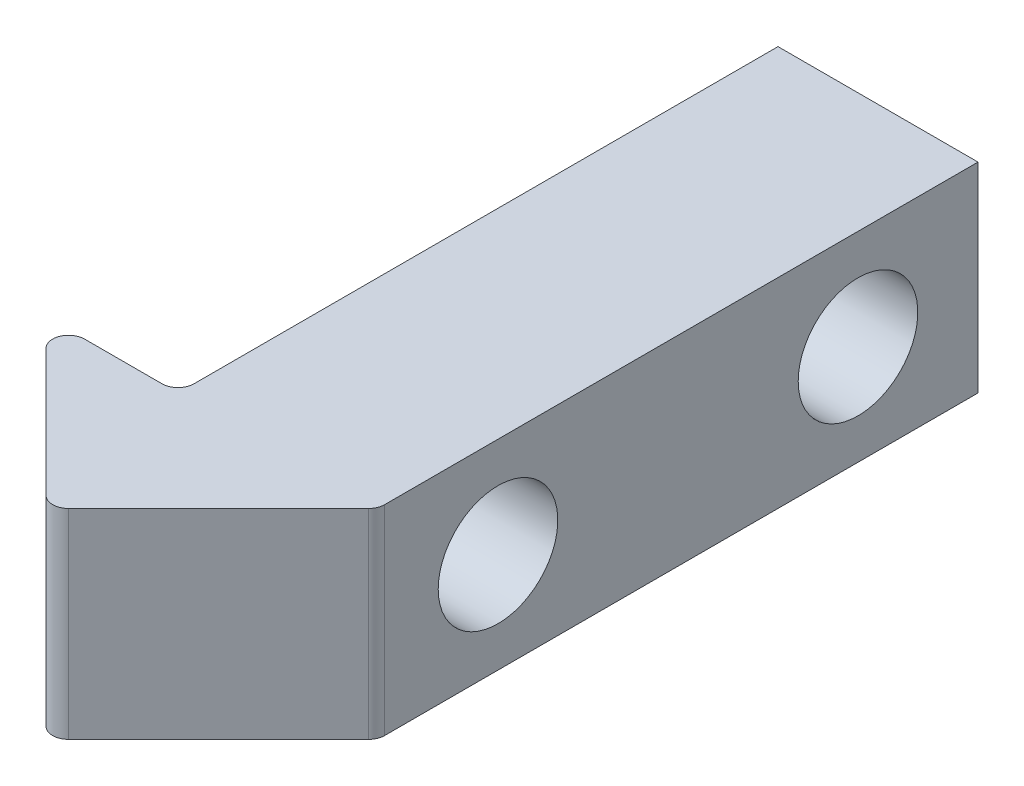
SolidWorks part; units mm, degrees
ref_plane "Front Plane" through (0, 0, 0) normal (0, 0, 1) x (1, 0, 0)
ref_plane "Top Plane" through (0, 0, 0) normal (0, 1, 0) x (1, 0, 0)
ref_plane "Right Plane" through (0, 0, 0) normal (1, 0, 0) x (0, 0, -1)
sketch "Sketch1" plane through (0, 0, 0) normal (0, 1, 0) x (1, 0, 0)
  line L0 (16.8387, -6.35) -> (11.5678, -11.6208)
  line L1 (-16.8387, -12.7) -> (16.8387, -12.7)
  line L2 (-16.8387, -12.7) -> (-16.8387, 12.7)
  line L3 (-16.8387, 12.7) -> (16.8387, 12.7)
  line L4 (16.8387, -12.7) -> (16.8387, 12.7)
  line L5 (-16.8387, -12.7) -> (16.8387, 12.7) construction
  line L6 (-16.8387, 12.7) -> (16.8387, -12.7) construction
  line L7 (-16.8387, 12.7) -> (10.4887, 12.7)
  line L8 (-16.8387, 12.7) -> (-16.8387, -6.35)
  line L9 (-16.8387, -6.35) -> (10.4887, -6.35)
  line L10 (10.4887, 12.7) -> (10.4887, -6.35)
  line L11 (11.5678, -11.6208) -> (6.297, -6.35)
  point P0 (0, 0)
  point P9 (16.8387, -6.35)
  point P14 (0, 0)
  dimension "D1" = 25.4
  dimension "D2" = 6.35
  dimension "D3" = 6.35
  dimension "D4" = 7.4541
extrude "Boss-Extrude1" add sketch "Sketch1" along normal blind 6.35 contours L11 L0 L4 L3 L10 L9
sketch "Sketch2" plane through (10.4887, 0, 0) normal (-1, 0, 0) x (0, 0, 1)
  line L0 (-12.7, 6.35) -> (-12.7, 0) construction
  line L1 (6.35, 6.35) -> (6.35, 0) construction
  point P0 (-8.89, 3.175)
  point P1 (2.54, 3.175)
  point P6 (-12.7, 3.175)
  point P7 (0, 0)
  dimension "D1" = 3.81
  dimension "D2" = 3.81
hole_wizard "#6 Clearance Hole1" positions "Sketch3" profile "Sketch4" hole size "#6" standard "ANSI Inch"
sketch "Sketch3" plane through (10.4887, 0, 0) normal (-1, 0, 0) x (0, 0, 1)
  point P0 (-8.89, 3.175)
  point P3 (2.54, 3.175)
sketch "Sketch4" plane through (10.4887, 3.175, -8.89) normal (0, 1, 0) x (0, 0, 1)
  line L0 (0, 0) -> (0, 7.874)
  line L1 (0, 7.874) -> (1.8986, 6.7332)
  line L2 (1.8986, 6.7332) -> (1.8986, 0)
  line L5 (1.8986, 0) -> (0, 0)
  line L10 (0, 7.874) -> (-1.8987, 6.7332) construction
  line L11 (0, -6.35) -> (0, 107.95) construction
  dimension "Hole Dia." = 3.7973
  dimension "Hole Depth" = 7.874
  dimension "Drill Angle" = 118
fillet "Fillet1" radius 0.508 4 edges at (10.4887, 3.175, 6.35) (16.8387, 3.175, 6.35) (6.297, 3.175, 6.35) (11.5678, 3.175, 11.6208)
